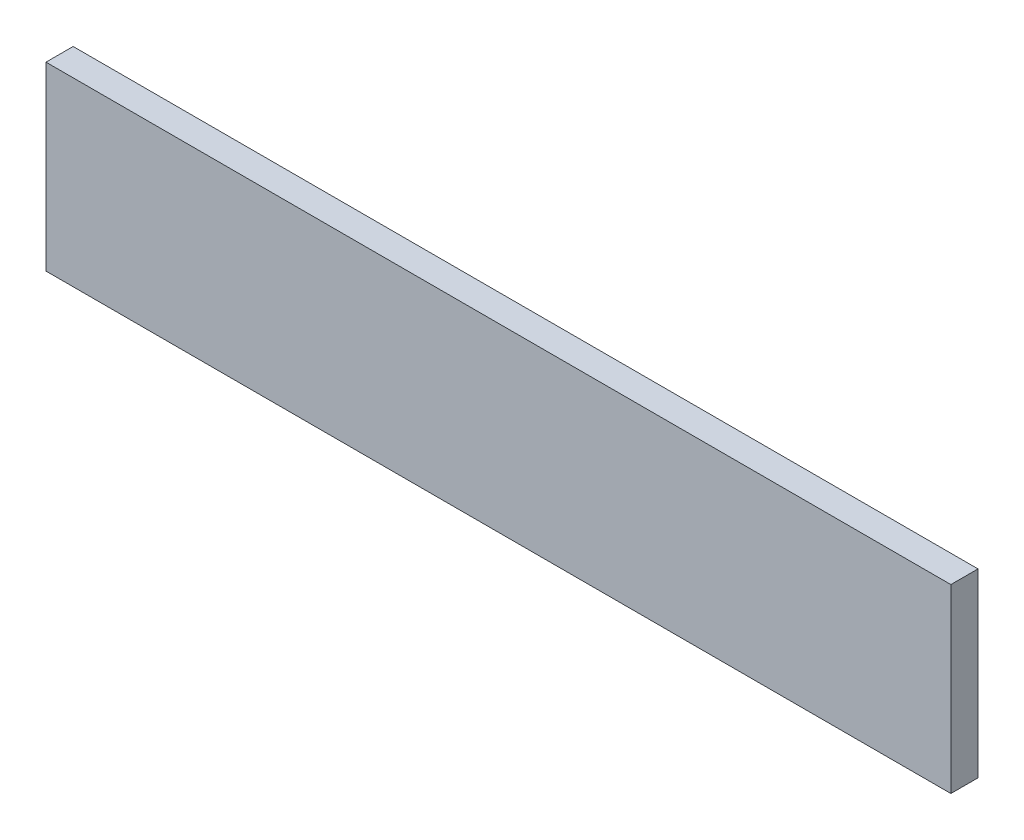
SolidWorks part; units mm, degrees
ref_plane "Face" through (0, 0, 0) normal (0, 0, 1) x (1, 0, 0)
ref_plane "Dessus" through (0, 0, 0) normal (0, 1, 0) x (1, 0, 0)
ref_plane "Droite" through (0, 0, 0) normal (1, 0, 0) x (0, 0, -1)
sketch "Esquisse1" plane through (0, 0, 0) normal (0, 0, 1) x (1, 0, 0)
  line L1 (141, -36.4613) -> (41, -36.4613)
  line L2 (141, -36.4613) -> (141, -16.4613)
  line L3 (141, -16.4613) -> (41, -16.4613)
  line L4 (41, -36.4613) -> (41, -16.4613)
  dimension "D1" = 100
  dimension "D2" = 20
extrude "Base-Extrusion" add sketch "Esquisse1" along normal blind 3
